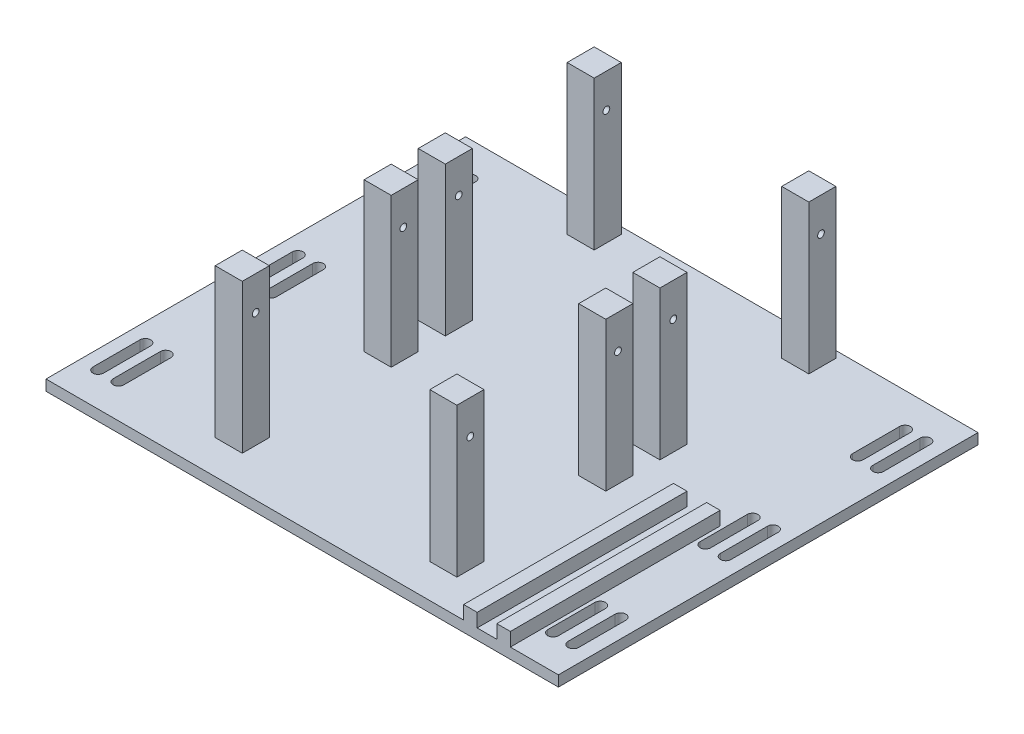
SolidWorks part; units mm, degrees
ref_plane "Front Plane" through (0, 0, 0) normal (0, 0, 1) x (1, 0, 0)
ref_plane "Top Plane" through (0, 0, 0) normal (0, 1, 0) x (1, 0, 0)
ref_plane "Right Plane" through (0, 0, 0) normal (1, 0, 0) x (0, 0, -1)
sketch "Sketch1" plane through (0, 0, 0) normal (0, 1, 0) x (1, 0, 0)
  line L1 (-48.0759, -39.37) -> (48.0759, -39.37)
  line L2 (-48.0759, -39.37) -> (-48.0759, 39.37)
  line L3 (-48.0759, 39.37) -> (48.0759, 39.37)
  line L4 (48.0759, -39.37) -> (48.0759, 39.37)
  line L5 (-48.0759, -39.37) -> (48.0759, 39.37) construction
  line L6 (-48.0759, 39.37) -> (48.0759, -39.37) construction
  point P0 (0, 0)
  dimension "D1" = 96.1517
  dimension "D2" = 78.74
extrude "Base Plate" add sketch "Sketch1" along normal blind 2
sketch "Sketch2" plane through (0, 2, 0) normal (0, 1, 0) x (1, 0, 0)
  line L1 (-48.0759, -39.37) -> (48.0759, -39.37) construction
  line L2 (22.6759, -33.02) -> (17.5959, -33.02)
  line L3 (22.6759, -33.02) -> (22.6759, -27.94)
  line L4 (22.6759, -27.94) -> (17.5959, -27.94)
  line L5 (17.5959, -33.02) -> (17.5959, -27.94)
  line L6 (22.6759, -5.08) -> (17.5959, -5.08)
  line L7 (22.6759, -5.08) -> (22.6759, 0)
  line L8 (22.6759, 0) -> (17.5959, 0)
  line L9 (17.5959, -5.08) -> (17.5959, 0)
  line L10 (48.0759, -39.37) -> (48.0759, 39.37) construction
  dimension "D1" = 6.35
  dimension "D2" = 22.86
  dimension "D3" = 25.4
  dimension "D4" = 5.08
  dimension "D5" = 5.08
extrude "Servo Supports" add sketch "Sketch2" along normal blind 27.94
sketch "Sketch3" plane through (22.6759, 0, 0) normal (1, 0, 0) x (0, 0, -1)
  line L0 (-33.02, 29.94) -> (-27.94, 29.94) construction
  line L1 (-27.94, 29.94) -> (-27.94, 2) construction
  circle A0 centre (-30.5043, 23.59) radius 0.635
  circle A1 centre (-2.7929, 23.59) radius 0.635
  dimension "D1" = 1.27
  dimension "D2" = 27.7114
  dimension "D3" = 6.35
  dimension "D4" = 2.5643
extrude "Servo Mount Holes" cut sketch "Sketch3" against normal blind 12.7
sketch "Sketch4" plane through (0, 2, 0) normal (0, 1, 0) x (1, 0, 0)
  line L0 (44.5359, -24.17) -> (44.5359, -33.02) construction
  line L1 (45.5359, -24.17) -> (45.5359, -33.02)
  line L2 (43.5359, -24.17) -> (43.5359, -33.02)
  line L3 (44.5359, 33.02) -> (44.5359, 24.17) construction
  line L4 (45.5359, 33.02) -> (45.5359, 24.17)
  line L5 (43.5359, 33.02) -> (43.5359, 24.17)
  line L6 (-44.6308, -24.17) -> (-44.6308, -33.02) construction
  line L7 (-43.6309, -24.17) -> (-43.6309, -33.02)
  line L8 (-45.6308, -24.17) -> (-45.6308, -33.02)
  line L9 (-44.6309, 33.02) -> (-44.6309, 24.17) construction
  line L10 (-43.6309, 33.02) -> (-43.6309, 24.17)
  line L11 (-45.6308, 33.02) -> (-45.6308, 24.17)
  line L12 (48.0759, -39.37) -> (48.0759, 39.37) construction
  line L13 (-48.0759, -39.37) -> (48.0759, -39.37) construction
  line L14 (48.0759, 39.37) -> (-48.0759, 39.37) construction
  line L15 (44.5359, 4.425) -> (44.5359, -4.425) construction
  line L16 (45.5359, 4.425) -> (45.5359, -4.425)
  line L17 (43.5359, 4.425) -> (43.5359, -4.425)
  line L18 (44.5359, -24.17) -> (44.5359, -4.425) construction
  line L19 (44.5359, 4.425) -> (44.5359, 24.17) construction
  line L20 (-44.6309, 4.425) -> (-44.6309, -4.425) construction
  line L21 (-43.6309, 4.425) -> (-43.6309, -4.425)
  line L22 (-45.6309, 4.425) -> (-45.6309, -4.425)
  line L23 (-48.0759, 39.37) -> (-48.0759, -39.37) construction
  line L24 (40.7259, -24.17) -> (40.7259, -33.02) construction
  line L25 (41.7258, -24.17) -> (41.7258, -33.02)
  line L26 (39.7259, -24.17) -> (39.7259, -33.02)
  line L27 (40.7259, 33.02) -> (40.7259, 24.17) construction
  line L28 (41.7259, 33.02) -> (41.7259, 24.17)
  line L29 (39.7259, 33.02) -> (39.7259, 24.17)
  line L30 (40.7259, 4.425) -> (40.7259, -4.425) construction
  line L31 (41.7258, 4.425) -> (41.7258, -4.425)
  line L32 (39.7259, 4.425) -> (39.7259, -4.425)
  line L33 (-40.8208, -24.17) -> (-40.8208, -33.02) construction
  line L34 (-39.8208, -24.17) -> (-39.8208, -33.02)
  line L35 (-41.8209, -24.17) -> (-41.8209, -33.02)
  line L36 (-40.8209, 33.02) -> (-40.8209, 24.17) construction
  line L37 (-39.8209, 33.02) -> (-39.8209, 24.17)
  line L38 (-41.8209, 33.02) -> (-41.8209, 24.17)
  line L39 (-40.8209, 4.425) -> (-40.8209, -4.425) construction
  line L40 (-39.8209, 4.425) -> (-39.8209, -4.425)
  line L41 (-41.8209, 4.425) -> (-41.8209, -4.425)
  arc A0 (45.5359, -24.17) -> (43.5359, -24.17) centre (44.5359, -24.17) ccw
  arc A1 (43.5359, -33.02) -> (45.5359, -33.02) centre (44.5359, -33.02) ccw
  arc A2 (45.5359, 33.02) -> (43.5359, 33.02) centre (44.5359, 33.02) ccw
  arc A3 (43.5359, 24.17) -> (45.5359, 24.17) centre (44.5359, 24.17) ccw
  arc A4 (-43.6309, -24.17) -> (-45.6308, -24.17) centre (-44.6308, -24.17) ccw
  arc A5 (-45.6308, -33.02) -> (-43.6309, -33.02) centre (-44.6308, -33.02) ccw
  arc A6 (-43.6309, 33.02) -> (-45.6308, 33.02) centre (-44.6309, 33.02) ccw
  arc A7 (-45.6308, 24.17) -> (-43.6309, 24.17) centre (-44.6309, 24.17) ccw
  arc A8 (45.5359, 4.425) -> (43.5359, 4.425) centre (44.5359, 4.425) ccw
  arc A9 (43.5359, -4.425) -> (45.5359, -4.425) centre (44.5359, -4.425) ccw
  arc A10 (-43.6309, 4.425) -> (-45.6309, 4.425) centre (-44.6309, 4.425) ccw
  arc A11 (-45.6309, -4.425) -> (-43.6309, -4.425) centre (-44.6309, -4.425) ccw
  arc A12 (41.7258, -24.17) -> (39.7259, -24.17) centre (40.7259, -24.17) ccw
  arc A13 (39.7259, -33.02) -> (41.7258, -33.02) centre (40.7259, -33.02) ccw
  arc A14 (41.7259, 33.02) -> (39.7259, 33.02) centre (40.7259, 33.02) ccw
  arc A15 (39.7259, 24.17) -> (41.7259, 24.17) centre (40.7259, 24.17) ccw
  arc A16 (41.7258, 4.425) -> (39.7259, 4.425) centre (40.7259, 4.425) ccw
  arc A17 (39.7259, -4.425) -> (41.7258, -4.425) centre (40.7259, -4.425) ccw
  arc A18 (-39.8208, -24.17) -> (-41.8209, -24.17) centre (-40.8208, -24.17) ccw
  arc A19 (-41.8209, -33.02) -> (-39.8208, -33.02) centre (-40.8208, -33.02) ccw
  arc A20 (-39.8209, 33.02) -> (-41.8209, 33.02) centre (-40.8209, 33.02) ccw
  arc A21 (-41.8209, 24.17) -> (-39.8209, 24.17) centre (-40.8209, 24.17) ccw
  arc A22 (-39.8209, 4.425) -> (-41.8209, 4.425) centre (-40.8209, 4.425) ccw
  arc A23 (-41.8209, -4.425) -> (-39.8209, -4.425) centre (-40.8209, -4.425) ccw
  point P2 (44.5359, -28.595)
  point P9 (44.5359, 28.595)
  point P16 (-44.6309, -28.595)
  point P23 (-44.6309, 28.595)
  point P36 (44.5359, 0)
  point P47 (-44.6309, 0)
  point P58 (40.7259, -28.595)
  point P65 (40.7259, 28.595)
  point P72 (40.7259, 0)
  point P78 (-40.8209, -28.595)
  point P85 (-40.8209, 28.595)
  point P92 (-40.8209, 0)
  dimension "D1" = 8.85
  dimension "D2" = 2.54
  dimension "D3" = 6.35
  dimension "D4" = 2.54
  dimension "D5" = 2
  dimension "D6" = 6.35
  dimension "D7" = 2.445
  dimension "D8" = 2
  dimension "D9" = 2
extrude "Strap Holes" cut sketch "Sketch4" against normal up to next
sketch "Sketch5" plane through (0, 2, 0) normal (0, 1, 0) x (1, 0, 0)
  line L0 (-48.0759, 39.37) -> (-48.0759, -39.37) construction
  line L1 (-17.5959, -16.51) -> (-35.3759, -16.51) construction
  line L2 (-17.5959, -16.51) -> (-17.5959, 16.51) construction
  line L3 (-17.5959, 16.51) -> (-35.3759, 16.51) construction
  line L4 (-35.3759, -16.51) -> (-35.3759, 16.51) construction
  line L5 (-17.5959, -16.51) -> (-35.3759, 16.51) construction
  line L6 (-17.5959, 16.51) -> (-35.3759, -16.51) construction
  line L7 (-35.3759, 0) -> (-48.0759, 0) construction
  line L8 (-22.0409, -20.955) -> (-22.0409, -12.065)
  line L9 (-30.9309, -20.955) -> (-39.8209, -20.955)
  line L10 (-30.9309, -20.955) -> (-30.9309, -12.065)
  line L11 (-30.9309, -12.065) -> (-39.8209, -12.065)
  line L12 (-39.8209, -20.955) -> (-39.8209, -12.065)
  line L13 (-30.9309, -20.955) -> (-39.8209, -12.065) construction
  line L14 (-30.9309, -12.065) -> (-39.8209, -20.955) construction
  line L15 (-13.1509, -20.955) -> (-22.0409, -20.955)
  line L16 (-13.1509, -20.955) -> (-13.1509, -12.065)
  line L17 (-13.1509, -12.065) -> (-22.0409, -12.065)
  line L18 (-22.0409, 12.065) -> (-22.0409, 20.955)
  line L19 (-13.1509, 12.065) -> (-22.0409, 12.065)
  line L20 (-13.1509, 12.065) -> (-13.1509, 20.955)
  line L21 (-13.1509, 20.955) -> (-22.0409, 20.955)
  line L22 (-39.8209, 12.065) -> (-39.8209, 20.955)
  line L23 (-30.9309, 12.065) -> (-39.8209, 12.065)
  line L24 (-30.9309, 12.065) -> (-30.9309, 20.955)
  line L25 (-30.9309, 20.955) -> (-39.8209, 20.955)
  point P0 (-26.4858, 0)
  dimension "D1" = 33.02
  dimension "D2" = 17.78
  dimension "D3" = 12.7
  dimension "D4" = 8.89
  dimension "D5" = 2
  dimension "D6" = 2
extrude "Boss-Extrude3" [suppressed] add sketch "Sketch5" along normal blind 3
sketch "Sketch7" plane through (0, 0, 0) normal (0, -1, 0) x (1, 0, 0)
  line L0 (-39.8209, 20.955) -> (-30.9309, 12.065) construction
  line L1 (-30.9309, 20.955) -> (-39.8209, 12.065) construction
  line L3 (-32.6196, 18.1013) -> (-35.3759, 19.6926)
  line L4 (-30.9309, 20.955) -> (-39.8209, 20.955)
  line L5 (-39.8209, 20.955) -> (-39.8209, 12.065)
  line L6 (-39.8209, 12.065) -> (-30.9309, 12.065)
  line L7 (-30.9309, 12.065) -> (-30.9309, 20.955)
  line L8 (-30.9309, 20.955) -> (-39.8209, 20.955) construction
  line L9 (-39.8209, 20.955) -> (-39.8209, 12.065) construction
  line L10 (-39.8209, 12.065) -> (-30.9309, 12.065) construction
  line L11 (-30.9309, 12.065) -> (-30.9309, 20.955) construction
  line L12 (-39.8209, -12.065) -> (-39.8209, -20.955)
  line L13 (-39.8209, -20.955) -> (-30.9309, -20.955)
  line L14 (-30.9309, -20.955) -> (-30.9309, -12.065)
  line L15 (-30.9309, -12.065) -> (-39.8209, -12.065)
  line L16 (-39.8209, -12.065) -> (-39.8209, -20.955)
  line L17 (-39.8209, -20.955) -> (-30.9309, -20.955)
  line L18 (-30.9309, -20.955) -> (-30.9309, -12.065)
  line L19 (-30.9309, -12.065) -> (-39.8209, -12.065)
  line L20 (-22.0409, -12.065) -> (-22.0409, -20.955)
  line L21 (-22.0409, -20.955) -> (-13.1509, -20.955)
  line L22 (-13.1509, -20.955) -> (-13.1509, -12.065)
  line L23 (-13.1509, -12.065) -> (-22.0409, -12.065)
  line L24 (-22.0409, -12.065) -> (-22.0409, -20.955)
  line L25 (-22.0409, -20.955) -> (-13.1509, -20.955)
  line L26 (-13.1509, -20.955) -> (-13.1509, -12.065)
  line L27 (-13.1509, -12.065) -> (-22.0409, -12.065)
  line L28 (-22.0409, 20.955) -> (-22.0409, 12.065)
  line L29 (-22.0409, 12.065) -> (-13.1509, 12.065)
  line L30 (-13.1509, 12.065) -> (-13.1509, 20.955)
  line L31 (-13.1509, 20.955) -> (-22.0409, 20.955)
  line L32 (-22.0409, 20.955) -> (-22.0409, 12.065)
  line L33 (-22.0409, 12.065) -> (-13.1509, 12.065)
  line L34 (-13.1509, 12.065) -> (-13.1509, 20.955)
  line L35 (-13.1509, 20.955) -> (-22.0409, 20.955)
  line L36 (-35.3759, 19.6926) -> (-38.1321, 18.1013)
  line L37 (-38.1321, 18.1013) -> (-38.1321, 14.9187)
  line L38 (-38.1321, 14.9187) -> (-35.3759, 13.3274)
  line L39 (-35.3759, 13.3274) -> (-32.6196, 14.9187)
  line L40 (-32.6196, 14.9187) -> (-32.6196, 18.1013)
  circle A0 centre (-35.3759, 16.51) radius 2.7562 construction
  dimension "D5" = 5.5125
  dimension "D1" = 0
  dimension "D2" = 0
  dimension "D3" = 0
  dimension "D4" = 0
extrude "Cut-Extrude3" [suppressed] cut sketch "Sketch7" against normal blind 3.175 contours L39 L40 L3 L36 L37 L38
pattern_linear "LPattern1" [suppressed] count 2 spacing 17.78 count 2 spacing 33.02
sketch "Sketch10" [suppressed] plane through (0, 5, 0) normal (0, 1, 0) x (1, 0, 0)
  line L0 (-19.177, -12.065) -> (-19.177, -20.955) construction
  line L1 (-19.177, 12.065) -> (-10.287, 12.065) construction
  line L4 (-19.177, 20.955) -> (-19.177, 12.065) construction
  line L5 (-1.397, -20.955) -> (7.493, -20.955) construction
  point P0 (-14.732, -16.51)
  point P1 (-14.732, 16.51)
  point P2 (3.048, 16.51)
  point P3 (3.048, -16.51)
  point P6 (-19.177, -16.51)
  point P9 (-14.732, 12.065)
  point P15 (-19.177, 16.51)
  point P18 (3.048, -20.955)
hole_wizard "#2 Clearance Hole1" [suppressed] positions "Sketch9" profile "Sketch8" hole size "#2" standard "ANSI Inch"
sketch "Sketch9" [suppressed] plane through (0, 5, 0) normal (0, 1, 0) x (1, 0, 0)
  point P0 (-14.732, -16.51)
  point P3 (3.048, -16.51)
  point P6 (-14.732, 16.51)
  point P9 (3.048, 16.51)
sketch "Sketch8" plane through (-14.732, 5, 16.51) normal (1, 0, 0) x (0, 0, 1)
  line L0 (0, 0) -> (0, 5)
  line L1 (0, 5) -> (1.7192, 5)
  line L2 (1.7192, 5) -> (1.7192, 0)
  line L5 (1.7192, 0) -> (0, 0)
  line L11 (0, -6.35) -> (0, 107.95) construction
  dimension "Thru Hole Dia." = 3.4384
  dimension "Thru Hole Depth" = 5
mirror "Servo Mount Mirror" about plane through (0, 0, 0) normal (1, 0, 0) of "Servo Mount Holes", "Servo Supports"
pattern_linear "Servo Mount Spacing" count 2 spacing 38.1 along (0, 0, -1) of "Servo Mount Mirror", "Servo Supports", "Servo Mount Holes"
sketch "Sketch11" plane through (0, 2, 0) normal (0, 1, 0) x (1, 0, 0)
  line L0 (-48.0759, 0) -> (48.0759, 0) construction
  line L1 (-48.0759, 39.37) -> (-48.0759, -39.37) construction
  line L2 (48.0759, -39.37) -> (48.0759, 39.37) construction
  line L3 (32.8359, 0) -> (32.8359, -39.37) construction
  line L5 (-48.0759, -39.37) -> (48.0759, -39.37) construction
  line L6 (36.5189, 0) -> (36.5189, -39.37) construction
  line L7 (22.6759, -33.02) -> (22.6759, -27.94) construction
  line L10 (32.8359, 0) -> (30.2958, 0)
  line L11 (32.8359, 0) -> (32.8359, -39.37)
  line L12 (32.8359, -39.37) -> (30.2958, -39.37)
  line L13 (30.2958, 0) -> (30.2958, -39.37)
  line L14 (36.5189, 0) -> (39.0588, 0)
  line L15 (36.5189, 0) -> (36.5189, -39.37)
  line L16 (36.5189, -39.37) -> (39.0589, -39.37)
  line L17 (39.0588, 0) -> (39.0589, -39.37)
  dimension "D1" = 10.16
  dimension "D2" = 3.683
  dimension "D3" = 2.54
  dimension "D4" = 2.54
extrude "Rack Rails" add sketch "Sketch11" along normal blind 2.54
